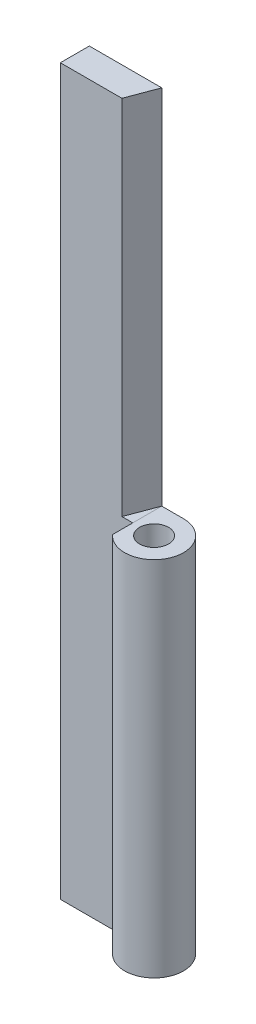
SolidWorks part; units mm, degrees
ref_plane "Front Plane" through (0, 0, 0) normal (0, 0, 1) x (1, 0, 0)
ref_plane "Top Plane" through (0, 0, 0) normal (0, 1, 0) x (1, 0, 0)
ref_plane "Right Plane" through (0, 0, 0) normal (1, 0, 0) x (0, 0, -1)
sketch "Sketch1" plane through (0, 0, 0) normal (0, 0, 1) x (1, 0, 0)
  line L1 (0, 0) -> (5, 0)
  line L2 (0, 0) -> (0, -50)
  line L3 (0, -50) -> (5, -50)
  line L4 (5, 0) -> (5, -50)
  dimension "D1" = 5
  dimension "D2" = 50
extrude "Boss-Extrude1" add sketch "Sketch1" along normal blind 2
sketch "Sketch2" plane through (0, 0, 0) normal (0, 1, 0) x (1, 0, 0)
  line L0 (5, 0) -> (6.5, 0)
  line L2 (5, 0) -> (5, -3.4)
  arc A0 (5, -3.4) -> (6.5, 0) centre (6.5, -2.0309) ccw
  dimension "D1" = 3.4
  dimension "D2" = 1.5
sketch "Sketch4" plane through (0, -50, 0) normal (0, -1, 0) x (1, 0, 0)
  line L4 (5, 0) -> (6.5, 0)
  line L5 (5, 3.4) -> (5, 0)
  line L6 (5, 0) -> (6.5, 0)
  line L7 (5, 3.4) -> (5, 0)
  arc A2 (6.5, 0) -> (5, 3.4) centre (6.5, 2.0309) ccw
  arc A3 (6.5, 0) -> (5, 3.4) centre (6.5, 2.0309) ccw
  dimension "D1" = 0
extrude "Boss-Extrude3" add sketch "Sketch4" against normal blind 25 separate body
sketch "Sketch5" plane through (0, -50, 0) normal (0, -1, 0) x (1, 0, 0)
  circle A0 centre (6.5, 2.0309) radius 1
  arc A1 (6.5, 0) -> (5, 3.4) centre (6.5, 2.0309) ccw construction
  dimension "D1" = 2
extrude "Cut-Extrude2" cut sketch "Sketch5" against normal through all
sketch "Sketch7" plane through (0, 0, 0) normal (0, 1, 0) x (1, 0, 0)
  line L1 (5, -2) -> (0, -2) construction
  line L3 (5, -2) -> (5, 0) construction
  line L4 (5, 0) -> (4.25, -2)
  line L5 (4.25, -2) -> (5, -2)
  line L6 (5, -2) -> (5, 0)
  dimension "D1" = 0.75
extrude "Cut-Extrude4" cut sketch "Sketch7" against normal up to surface (25 mm away) up to face at (6.5, -25, 1.0309)
